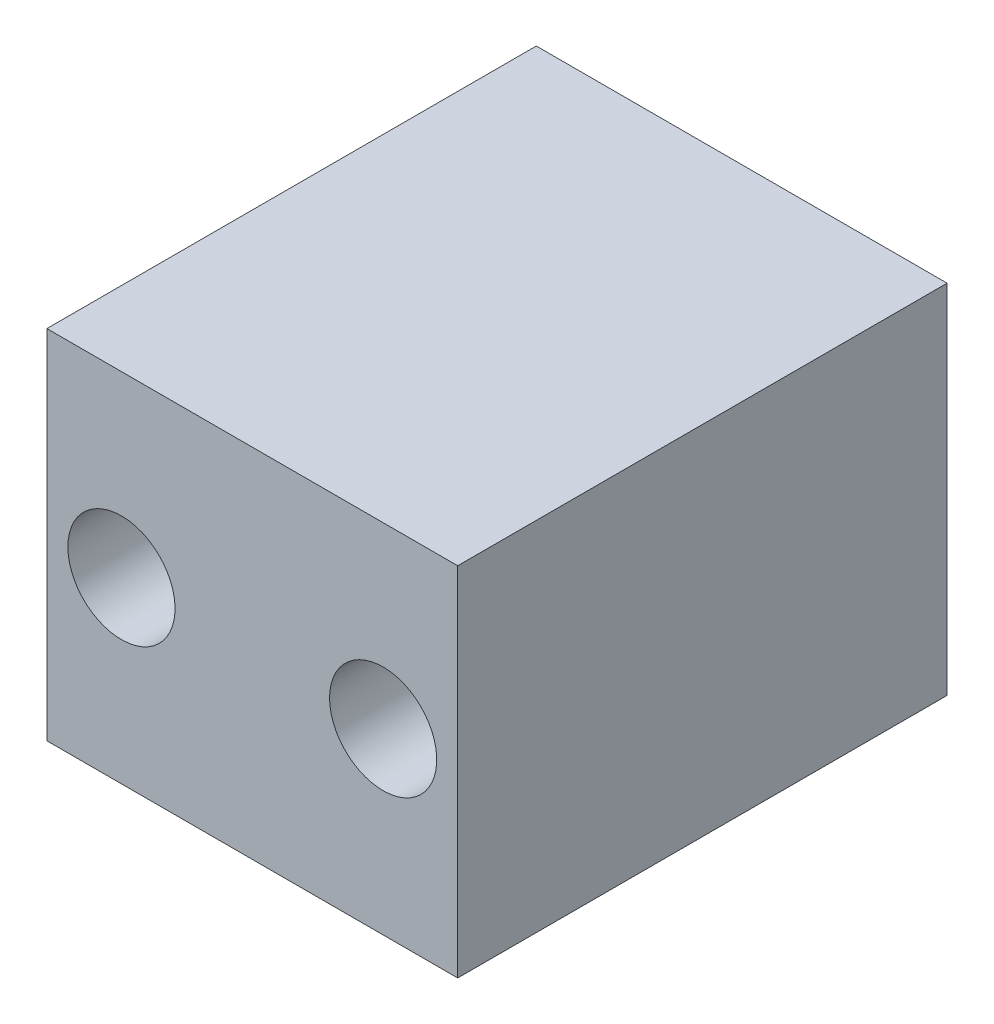
SolidWorks part; units mm, degrees
ref_plane "Front Plane" through (0, 0, 0) normal (0, 0, 1) x (1, 0, 0)
ref_plane "Top Plane" through (0, 0, 0) normal (0, 1, 0) x (1, 0, 0)
ref_plane "Right Plane" through (0, 0, 0) normal (1, 0, 0) x (0, 0, -1)
sketch "Sketch1" [suppressed] plane through (0, 0, 0) normal (0, 1, 0) x (1, 0, 0)
  line L1 (-9, 6.6) -> (9, 6.6)
  line L2 (-9, 6.6) -> (-9, -6.6)
  line L3 (-9, -6.6) -> (9, -6.6)
  line L4 (9, 6.6) -> (9, -6.6)
  line L5 (-9, 6.6) -> (9, -6.6) construction
  line L6 (-9, -6.6) -> (9, 6.6) construction
  point P0 (0, 0)
  dimension "D2" = 13.2
  dimension "D1" = 18
sketch "Sketch3" plane through (0, 0, 0) normal (0, 0, 1) x (1, 0, 0)
  line B0 (-5.75, 4.9972) -> (5.75, 4.9972)
  line B1 (-5.75, 4.9972) -> (-5.75, -4.9972)
  line B2 (-5.75, -4.9972) -> (5.75, -4.9972)
  line B3 (5.75, 4.9972) -> (5.75, -4.9972)
  circle B4 centre (3.6625, 0) radius 1.5
  circle B5 centre (-3.6625, 0) radius 1.5
sketch_block_instance "Block1-1"
sketch_block "Block1" parameters "D1"=11.5
extrude "Boss-Extrude2" add sketch "Sketch3" along normal blind 13.7
equation "\"supportThickness\"=1.5"
equation "\"pcbThickness\"= 1.6"
equation "\"sideWallThickness\"= 1.5"
equation "\"bottomWallThickness\"= 6.0"
equation "\"topWallThickness\"= 2.0"
equation "\"wallTolerance\"= 0.2"
equation "\"totalHeight\"= 220.50 + \"wallTolerance\""
equation "\"totalWidth\"= 12 * \"motorDiameter\" + 11 * \"motor2motorHorizontal\" + 2 * \"wallTolerance\""
equation "\"totalDepth\"= 4 * \"motorDiameter\" + 2 * \"pcbThickness\" + 1 * \"motor2motorHorizontal\" + 4 * 0.10 + 2 * \"wallTolerance\""
equation "\"pinHeight\"= 115"
equation "\"pinWidth\"= 4.85"
equation "\"electricalComponents\"=53.04"
equation "\"motorDiameter\"=6.0"
equation "\"res\"= 2.0"
equation "\"pcbWidth\"= 106.67"
equation "\"supportDistance\"= 10.0"
equation "\"pcbLength\"= 216.23"
equation "\"motorSmallDiameter\"= 3.5"
equation "\"motorSmallLength\"= 0.4"
equation "\"motorShaftDiameter\"= 2.0"
equation "\"motorShaftLength\"= 2.7"
equation "\"motorShaftFlatDist\"= 1.5"
equation "\"motorWireDiameter\"= 0.5"
equation "\"motorWireDistance\"= 3.20"
equation "\"encoderLength\"= 3.2"
equation "\"encoderWidth\"= 1.7"
equation "\"encoderDepth\"=1.1"
equation "\"encoderTolerance\"=0.15"
equation "\"encoderDistance\"=1.0"
equation "\"pcbToWall\"= \"motorDiameter\" + \"wallTolerance\""
equation "\"pcbToPcb\"= 2 * \"motorDiameter\" + \"wallTolerance\" + 1.0"
equation "\"bracketBlockWidth\"= 13.20"
equation "\"topBlockLength\"= 18"
equation "\"D1@Sketch1\"=\"topBlockLength\""
equation "\"D2@Sketch1\"=\"bracketBlockWidth\""
equation "\"bracketBlockHeight\"= 10.0"
equation "\"pcbExtension\"= 26.0"
equation "\"acrylicSideWallThickness\"= 2.0"
equation "\"smallBlockLength\"= 14"
equation "\"bottomBlockLength\"= 24"
equation "\"encoderToSwitchDistance\"= 7.35"
equation "\"encoderTicksSpacing\"= 0.65"
equation "\"motor2motorHorizontal\"= 1.0"
equation "\"motor2motorVertical\"= 1.80"
equation "\"length\"= 152.0"
